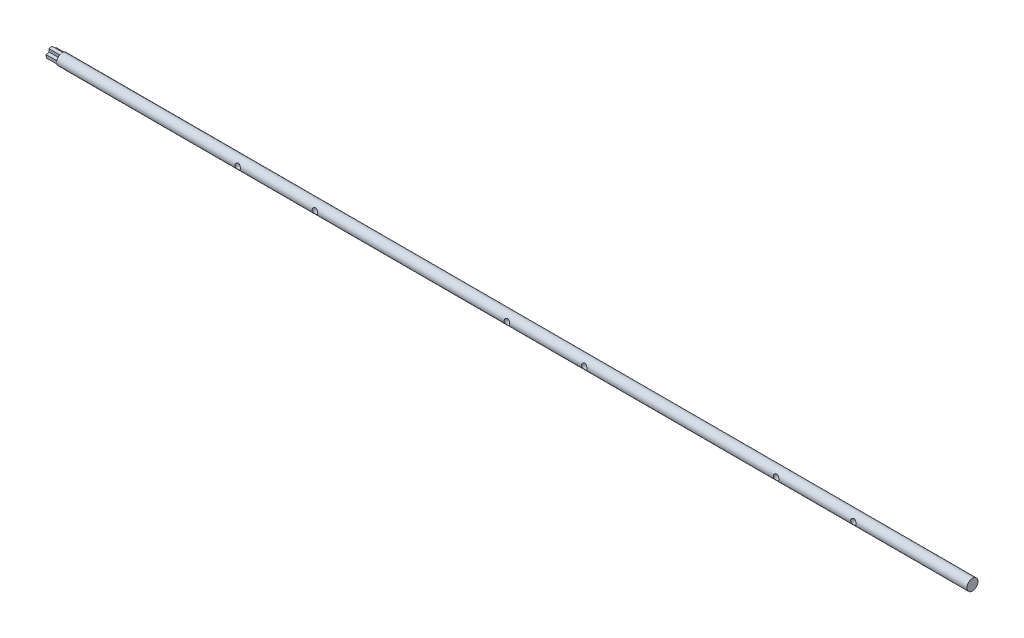
SolidWorks part; units mm, degrees
ref_plane "Front Plane" through (0, 0, 0) normal (0, 0, 1) x (1, 0, 0)
ref_plane "Top Plane" through (0, 0, 0) normal (0, 1, 0) x (1, 0, 0)
ref_plane "Right Plane" through (0, 0, 0) normal (1, 0, 0) x (0, 0, -1)
sketch "Sketch1" plane through (0, 0, 0) normal (0, 0, 1) x (1, 0, 0)
  line L0 (0, 0) -> (-27.6323, 0) construction
  line L1 (0, 0) -> (825, 0)
  line L2 (0, 0) -> (0, 5)
  line L3 (0, 5) -> (825, 5)
  line L4 (825, 0) -> (825, 5)
  dimension "D1" = 10
  dimension "D2" = 825
revolve "Revolve1" add sketch "Sketch1" angle 360 about L0
sketch "Sketch2" plane through (0, 0, 0) normal (-1, 0, 0) x (0, 0, 1)
  line L0 (-0.6526, -4.9572) -> (0.6526, 4.9572) construction
  line L1 (-4.2657, 2.0745) -> (-1.2914, 1.683)
  line L2 (-4.2657, 2.0745) -> (-4.6573, -0.8998)
  line L3 (-4.6573, -0.8998) -> (-1.683, -1.2914)
  line L4 (4.6573, 0.8998) -> (4.2657, -2.0745)
  line L5 (-0.8998, 4.6573) -> (2.0745, 4.2657)
  line L6 (-0.8998, 4.6573) -> (-1.2914, 1.683)
  line L7 (-2.0745, -4.2657) -> (0.8998, -4.6573)
  line L8 (2.0745, 4.2657) -> (1.683, 1.2914)
  line L9 (-4.9572, 0.6526) -> (4.9572, -0.6526) construction
  line L10 (1.2914, -1.683) -> (4.2657, -2.0745)
  line L11 (1.2914, -1.683) -> (0.8998, -4.6573)
  line L12 (-1.683, -1.2914) -> (-2.0745, -4.2657)
  line L13 (1.683, 1.2914) -> (4.6573, 0.8998)
  line L14 (0, 5) -> (0, -5) construction
  circle A1 centre (0, 0) radius 5 construction
  point P15 (0, 0)
  point P20 (0, 0)
  dimension "D1" = 10
  dimension "D2" = 9
  dimension "D3" = 7.5
extrude "Boss-Extrude1" add sketch "Sketch2" along normal blind 10
sketch "Sketch3" plane through (0, 0, 0) normal (0, 0, 1) x (1, 0, 0)
  line L0 (0, 0) -> (825, 0) construction
  line L1 (825, -5) -> (825, 5) construction
  line L2 (0, 5) -> (0, -5) construction
  line L3 (0, -4.6573) -> (0, -1.683) construction
  circle A0 centre (164, 0) radius 2.5
  circle A1 centre (234, 0) radius 2.5
  dimension "D1" = 5
  dimension "D3" = 234
  dimension "D2" = 164
extrude "Cut-Extrude1" cut sketch "Sketch3" against normal through all both and the other way through all
pattern_linear "LPattern1" count 3 spacing 244 along (1, 0, 0) of "Cut-Extrude1"
